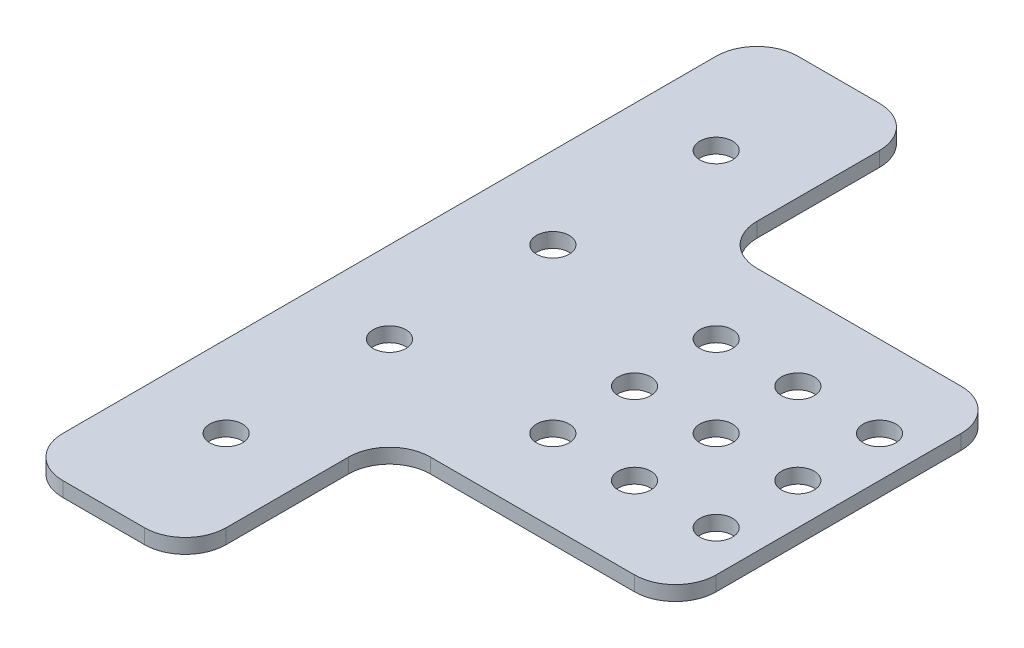
SolidWorks part; units mm, degrees
ref_plane "Front Plane" through (0, 0, 0) normal (0, 0, 1) x (1, 0, 0)
ref_plane "Top Plane" through (0, 0, 0) normal (0, 1, 0) x (1, 0, 0)
ref_plane "Right Plane" through (0, 0, 0) normal (1, 0, 0) x (0, 0, -1)
sketch "Sketch1" plane through (0, 0, 0) normal (0, 1, 0) x (1, 0, 0)
  line B0 (25.4, 114.3) -> (0, 114.3)
  line B1 (0, 114.3) -> (0, 0)
  line B2 (0, 0) -> (25.4, 0)
  line B3 (25.4, 0) -> (25.4, 31.75)
  line B4 (25.4, 31.75) -> (69.85, 31.75)
  line B5 (69.85, 31.75) -> (69.85, 82.55)
  line B6 (69.85, 82.55) -> (25.4, 82.55)
  line B7 (25.4, 82.55) -> (25.4, 114.3)
  circle B8 centre (12.7, 95.25) radius 2.54
  circle B9 centre (12.7, 69.85) radius 2.54
  circle B10 centre (12.7, 44.45) radius 2.54
  circle B11 centre (12.7, 19.05) radius 2.54
  circle B12 centre (38.1, 69.85) radius 2.54
  circle B13 centre (50.8, 69.85) radius 2.54
  circle B14 centre (63.5, 69.85) radius 2.54
  circle B15 centre (50.8, 57.15) radius 2.54
  circle B16 centre (63.5, 57.15) radius 2.54
  circle B17 centre (50.8, 44.45) radius 2.54
  circle B18 centre (63.5, 44.45) radius 2.54
  circle B19 centre (38.1, 57.15) radius 2.54
  circle B20 centre (38.1, 44.45) radius 2.54
sketch_block_instance "Block-2x2_DriveBase_Guessest-1"
sketch_block "Block-2x2_DriveBase_Guessest" parameters "D5"=5.08, "D11"=5.08, "D1"=50.8, "D2"=31.75, "D3"=31.75, "D4"=69.85, "D6"=12.7, "D7"=19.05, "D8"=25.4, "D9"=12.7, "D10"=31.75, "D12"=12.7, "D13"=12.7
extrude "Boss-Extrude1" add sketch "Sketch1" along normal blind 2.286
fillet "Fillet1" radius 6.35 8 edges at (25.4, 1.143, -82.55) (69.85, 1.143, -82.55) (69.85, 1.143, -31.75) (25.4, 1.143, -31.75) (25.4, 1.143, 0) (0, 1.143, -114.3) (25.4, 1.143, -114.3) (0, 1.143, 0)
